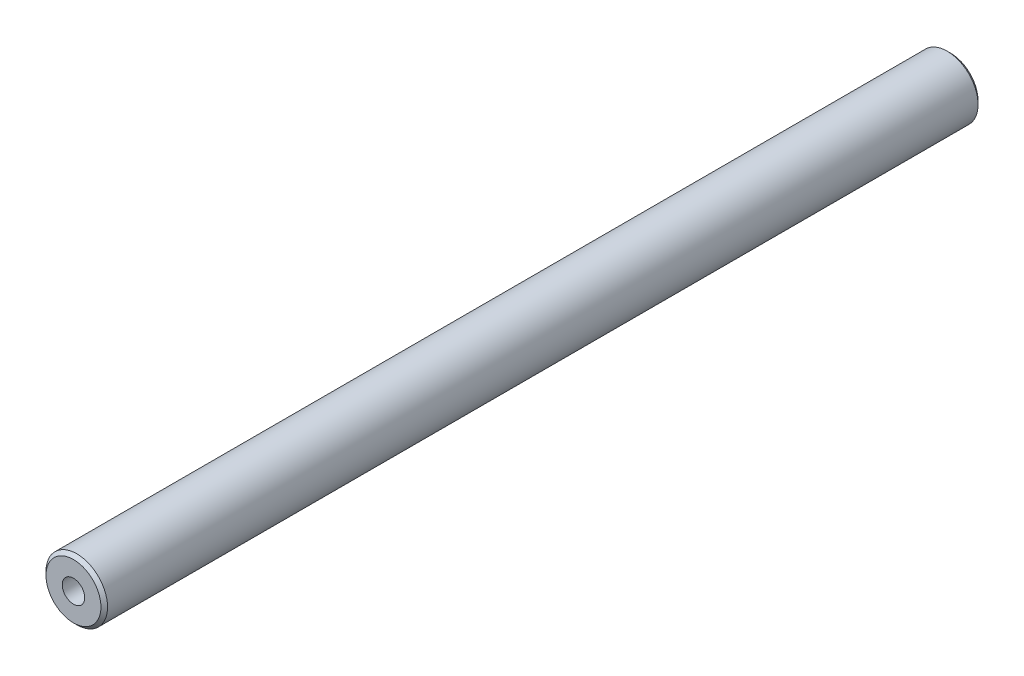
SolidWorks part; units mm, degrees
material "6061-T6 (SS)"
ref_plane "Front Plane" through (0, 0, 0) normal (0, 0, 1) x (1, 0, 0)
ref_plane "Top Plane" through (0, 0, 0) normal (0, 1, 0) x (1, 0, 0)
ref_plane "Right Plane" through (0, 0, 0) normal (1, 0, 0) x (0, 0, -1)
sketch "Sketch1" plane through (0, 0, 0) normal (1, 0, 0) x (0, 0, -1)
  line L0 (0, 0) -> (0, 4.7307)
  line L1 (0, 4.7307) -> (134.8223, 4.7307)
  line L7 (134.8223, 0) -> (0, 0)
  line L8 (0, 0) -> (-50000, 0) construction
  line L11 (134.8223, 0) -> (134.8223, 4.7307)
  dimension "D1" = 9.4615
  dimension "D6" = 134.8223
revolve "Revolve1" add sketch "Sketch1" angle 360 about L8
sketch "Sketch6" plane through (0, 0, 0) normal (0, 0, 1) x (1, 0, 0)
  circle A0 centre (0, 0) radius 3.7602
chamfer "Chamfer1" distance 0.508 angle 45 2 edges at (-4.7307, 0, -134.8223) (-4.7307, 0, 0)
hole_wizard "#8-32 Tapped Hole1" positions "Sketch15" profile "Sketch14" tap size "#8-32" standard "ANSI Inch"
sketch "Sketch15" plane through (0, 0, 0) normal (0, 0, 1) x (1, 0, 0)
  point P0 (0, 0)
sketch "Sketch14" plane through (0, 0, 0) normal (1, 0, 0) x (0, -1, 0)
  line L0 (0, 0) -> (0, 11.7566)
  line L1 (0, 11.7566) -> (1.7272, 10.7188)
  line L2 (1.7272, 10.7188) -> (1.7272, 0)
  line L5 (1.7272, 0) -> (0, 0)
  line L10 (0, 11.7566) -> (-1.7272, 10.7188) construction
  line L11 (0, -6.35) -> (0, 107.95) construction
  dimension "Tap Drill Dia." = 3.4544
  dimension "Tap Drill Depth" = 10.7188
  dimension "Drill Angle" = 118
cosmetic thread "Hole Thread1" parameters "D1"=8.3312, "D2"=4.1656
hole_wizard "#8-32 Tapped Hole3" positions "3DSketch12" profile "Sketch18" tap size "#8-32" standard "ANSI Inch"
sketch3d "3DSketch12"
  line L0 (0, 0, -134.3143) -> (0, 0, -134.8223) construction
  point P0 (0, 0, -134.8223)
sketch "Sketch18" plane through (0, 0, -134.8223) normal (1, 0, 0) x (0, 1, 0)
  line L0 (0, 0) -> (0, 11.7566)
  line L1 (0, 11.7566) -> (1.7272, 10.7188)
  line L2 (1.7272, 10.7188) -> (1.7272, 0)
  line L5 (1.7272, 0) -> (0, 0)
  line L10 (0, 11.7566) -> (-1.7272, 10.7188) construction
  line L11 (0, -6.35) -> (0, 107.95) construction
  dimension "Tap Drill Dia." = 3.4544
  dimension "Tap Drill Depth" = 10.7188
  dimension "Drill Angle" = 118
cosmetic thread "Hole Thread3" parameters "D1"=8.3312, "D2"=4.1656
